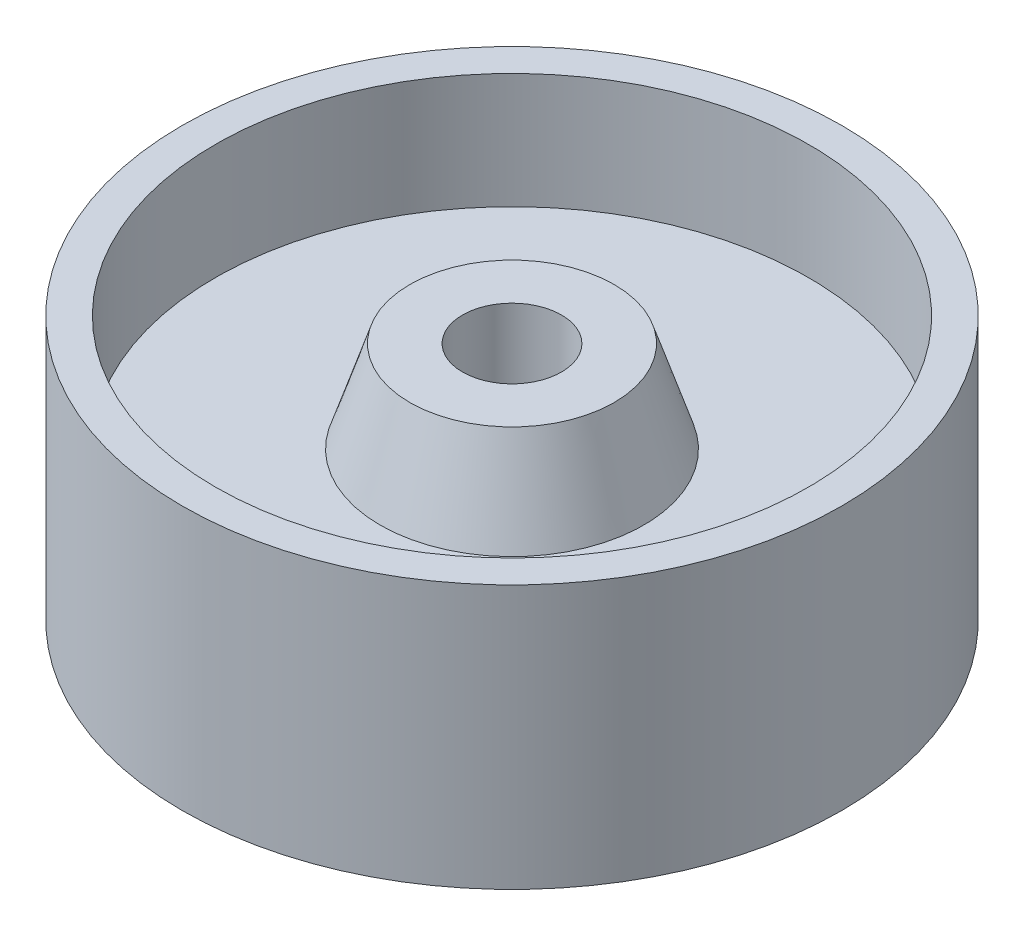
SolidWorks part; units mm, degrees
ref_plane "Front Plane" through (0, 0, 0) normal (0, 0, 1) x (1, 0, 0)
ref_plane "Top Plane" through (0, 0, 0) normal (0, 1, 0) x (1, 0, 0)
ref_plane "Right Plane" through (0, 0, 0) normal (1, 0, 0) x (0, 0, -1)
sketch "Sketch1" plane through (0, 0, 0) normal (1, 0, 0) x (0, 0, -1)
  line L0 (0, 2.4536) -> (0, -2.225) construction
  line L1 (-3.0929, 0) -> (2.6857, 0) construction
  line L2 (-2.5, -1) -> (-2.5, 1)
  line L3 (-2.5, 1) -> (-2.25, 1)
  line L4 (-2.25, 1) -> (-2.25, 0.125)
  line L5 (-2.25, 0.125) -> (-1, 0.125)
  line L6 (-1, 0.125) -> (-0.775, 0.8175)
  line L7 (-0.775, 0.8175) -> (-0.375, 0.8175)
  line L8 (-0.375, 0.8175) -> (-0.375, -0.8175)
  line L9 (-0.775, -0.8175) -> (-0.375, -0.8175)
  line L10 (-1, -0.125) -> (-0.775, -0.8175)
  line L11 (-2.25, -0.125) -> (-1, -0.125)
  line L12 (-2.25, -1) -> (-2.25, -0.125)
  line L13 (-2.5, -1) -> (-2.25, -1)
  point P3 (-0.6257, 0.9471)
  point P4 (0, 0)
  point P16 (-0.375, 0)
  point P21 (-2.5, 0)
  dimension "D1" = 5
  dimension "D2" = 2
  dimension "D3" = 0.75
  dimension "D4" = 0.4
  dimension "D5" = 0.25
  dimension "D6" = 0.25
  dimension "D7" = 18
  dimension "D8" = 1
revolve "Revolve1" add sketch "Sketch1" angle 360 about L0
